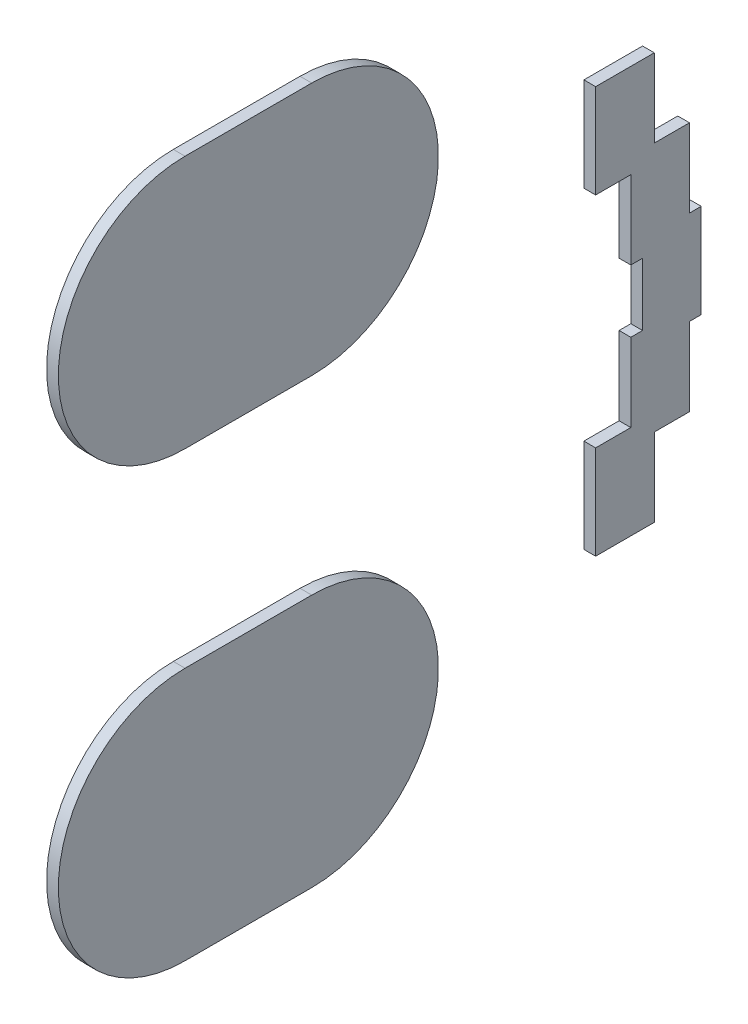
SolidWorks part; units mm, degrees
ref_plane "Front Plane" through (0, 0, 0) normal (0, 0, 1) x (1, 0, 0)
ref_plane "Top Plane" through (0, 0, 0) normal (0, 1, 0) x (1, 0, 0)
ref_plane "Right Plane" through (0, 0, 0) normal (1, 0, 0) x (0, 0, -1)
ref_plane "PZ_p30_810" through (0, 0, 30.81) normal (0, 0, 1) x (1, 0, 0)
sketch "S_box1" plane through (0, 0, 30.81) normal (0, 0, 1) x (1, 0, 0)
  line L0 (29.5, 2.43) -> (29.8, 2.43)
  line L1 (29.8, 2.43) -> (29.8, 8.91)
  line L2 (29.8, 8.91) -> (29.5, 8.91)
  line L3 (29.5, 8.91) -> (29.5, 2.43)
  dimension "P1" = 29.5
  dimension "P2" = 2.43
  dimension "P3" = 29.8
  dimension "P4" = 2.43
  dimension "P5" = 29.8
  dimension "P6" = 8.91
  dimension "P7" = 29.5
  dimension "P8" = 8.91
extrude "Boss_1" add sketch "S_box1" along normal blind 3.24
ref_plane "PX_p29_500" through (29.5, 0, 0) normal (1, 0, 0) x (0, 0, -1)
sketch "S_cyl2" plane through (29.5, 0, 0) normal (1, 0, 0) x (0, 0, -1)
  circle A0 centre (-30.81, 5.67) radius 3.24
  dimension "D1_S_cyl2" = 6.48
  dimension "P2" = 30.81
  dimension "P3" = 5.67
extrude "Boss_2" add sketch "S_cyl2" along normal blind 0.3
sketch "S_cyl3" plane through (29.5, 0, 0) normal (1, 0, 0) x (0, 0, -1)
  circle A0 centre (-34.05, 5.67) radius 3.24
  dimension "D1_S_cyl3" = 6.48
  dimension "P2" = 34.05
  dimension "P3" = 5.67
extrude "Boss_3" add sketch "S_cyl3" along normal blind 0.3
sketch "S_box4" plane through (0, 0, 30.81) normal (0, 0, 1) x (1, 0, 0)
  line L0 (29.5, -8.91) -> (29.8, -8.91)
  line L1 (29.8, -8.91) -> (29.8, -2.43)
  line L2 (29.8, -2.43) -> (29.5, -2.43)
  line L3 (29.5, -2.43) -> (29.5, -8.91)
  dimension "P1" = 29.5
  dimension "P2" = 8.91
  dimension "P3" = 29.8
  dimension "P4" = 8.91
  dimension "P5" = 29.8
  dimension "P6" = 2.43
  dimension "P7" = 29.5
  dimension "P8" = 2.43
extrude "Boss_4" add sketch "S_box4" along normal blind 3.24
sketch "S_cyl5" plane through (29.5, 0, 0) normal (1, 0, 0) x (0, 0, -1)
  circle A0 centre (-30.81, -5.67) radius 3.24
  dimension "D1_S_cyl5" = 6.48
  dimension "P2" = 30.81
  dimension "P3" = 5.67
extrude "Boss_5" add sketch "S_cyl5" along normal blind 0.3
sketch "S_cyl6" plane through (29.5, 0, 0) normal (1, 0, 0) x (0, 0, -1)
  circle A0 centre (-34.05, -5.67) radius 3.24
  dimension "D1_S_cyl6" = 6.48
  dimension "P2" = 34.05
  dimension "P3" = 5.67
extrude "Boss_6" add sketch "S_cyl6" along normal blind 0.3
ref_plane "PZ_p22_050" through (0, 0, 22.05) normal (0, 0, 1) x (1, 0, 0)
sketch "S_box7" plane through (0, 0, 22.05) normal (0, 0, 1) x (1, 0, 0)
  line L0 (29.5, -5.2) -> (29.8, -5.2)
  line L1 (29.8, -5.2) -> (29.8, -2.8)
  line L2 (29.8, -2.8) -> (29.5, -2.8)
  line L3 (29.5, -2.8) -> (29.5, -5.2)
  dimension "P1" = 29.5
  dimension "P2" = 5.2
  dimension "P3" = 29.8
  dimension "P4" = 5.2
  dimension "P5" = 29.8
  dimension "P6" = 2.8
  dimension "P7" = 29.5
  dimension "P8" = 2.8
extrude "Boss_7" add sketch "S_box7" along normal blind 1.5
ref_plane "PZ_p21_150" through (0, 0, 21.15) normal (0, 0, 1) x (1, 0, 0)
sketch "S_box8" plane through (0, 0, 21.15) normal (0, 0, 1) x (1, 0, 0)
  line L0 (29.5, -3.2) -> (29.8, -3.2)
  line L1 (29.8, -3.2) -> (29.8, -0.8)
  line L2 (29.8, -0.8) -> (29.5, -0.8)
  line L3 (29.5, -0.8) -> (29.5, -3.2)
  dimension "P1" = 29.5
  dimension "P2" = 3.2
  dimension "P3" = 29.8
  dimension "P4" = 3.2
  dimension "P5" = 29.8
  dimension "P6" = 0.8
  dimension "P7" = 29.5
  dimension "P8" = 0.8
extrude "Boss_8" add sketch "S_box8" along normal blind 1.5
ref_plane "PZ_p20_850" through (0, 0, 20.85) normal (0, 0, 1) x (1, 0, 0)
sketch "S_box9" plane through (0, 0, 20.85) normal (0, 0, 1) x (1, 0, 0)
  line L0 (29.5, -1.2) -> (29.8, -1.2)
  line L1 (29.8, -1.2) -> (29.8, 1.2)
  line L2 (29.8, 1.2) -> (29.5, 1.2)
  line L3 (29.5, 1.2) -> (29.5, -1.2)
  dimension "P1" = 29.5
  dimension "P2" = 1.2
  dimension "P3" = 29.8
  dimension "P4" = 1.2
  dimension "P5" = 29.8
  dimension "P6" = 1.2
  dimension "P7" = 29.5
  dimension "P8" = 1.2
extrude "Boss_9" add sketch "S_box9" along normal blind 1.5
sketch "S_box10" plane through (0, 0, 21.15) normal (0, 0, 1) x (1, 0, 0)
  line L0 (29.5, 0.8) -> (29.8, 0.8)
  line L1 (29.8, 0.8) -> (29.8, 3.2)
  line L2 (29.8, 3.2) -> (29.5, 3.2)
  line L3 (29.5, 3.2) -> (29.5, 0.8)
  dimension "P1" = 29.5
  dimension "P2" = 0.8
  dimension "P3" = 29.8
  dimension "P4" = 0.8
  dimension "P5" = 29.8
  dimension "P6" = 3.2
  dimension "P7" = 29.5
  dimension "P8" = 3.2
extrude "Boss_10" add sketch "S_box10" along normal blind 1.5
sketch "S_box11" plane through (0, 0, 22.05) normal (0, 0, 1) x (1, 0, 0)
  line L0 (29.5, 2.8) -> (29.8, 2.8)
  line L1 (29.8, 2.8) -> (29.8, 5.2)
  line L2 (29.8, 5.2) -> (29.5, 5.2)
  line L3 (29.5, 5.2) -> (29.5, 2.8)
  dimension "P1" = 29.5
  dimension "P2" = 2.8
  dimension "P3" = 29.8
  dimension "P4" = 2.8
  dimension "P5" = 29.8
  dimension "P6" = 5.2
  dimension "P7" = 29.5
  dimension "P8" = 5.2
extrude "Boss_11" add sketch "S_box11" along normal blind 1.5
equation "\"plate_t\" = 3"
equation "\"clearance\" = 0.4"
